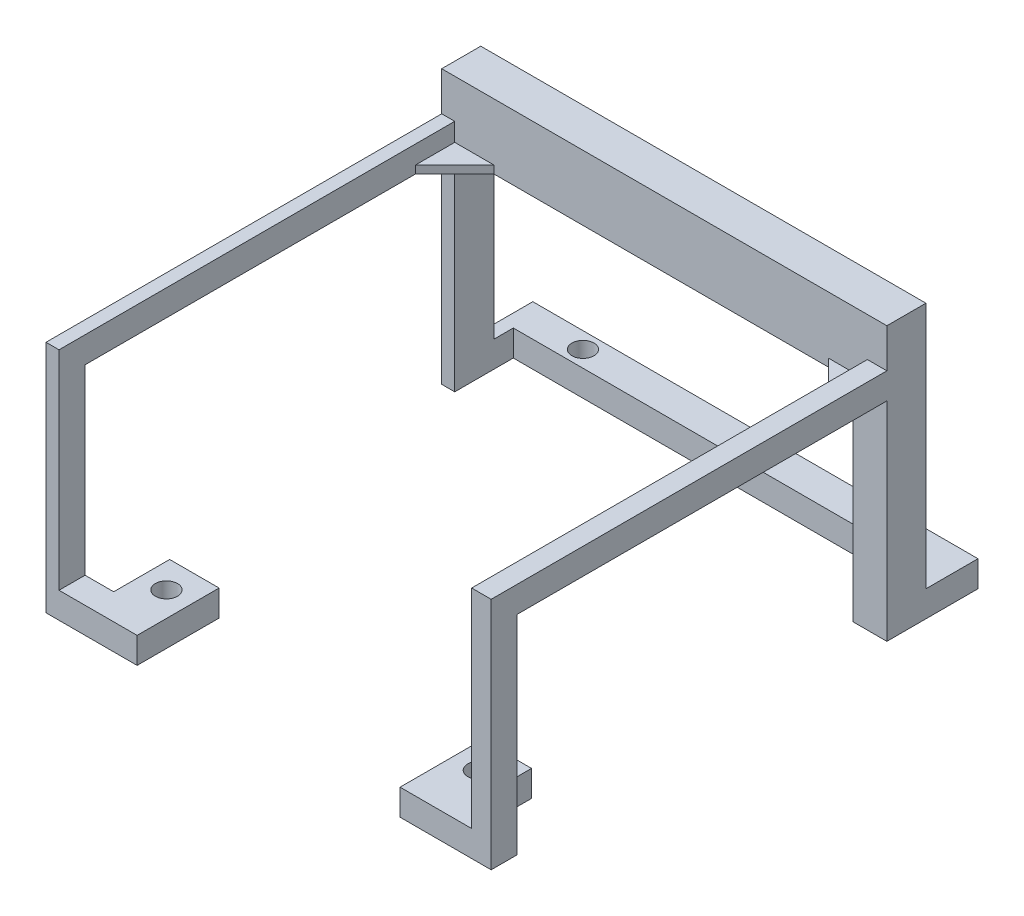
SolidWorks part; units mm, degrees
ref_plane "Front Plane" through (0, 0, 0) normal (0, 0, 1) x (1, 0, 0)
ref_plane "Top Plane" through (0, 0, 0) normal (0, 1, 0) x (1, 0, 0)
ref_plane "Right Plane" through (0, 0, 0) normal (1, 0, 0) x (0, 0, -1)
sketch "Sketch1" plane through (0, 0, 0) normal (0, 1, 0) x (1, 0, 0)
  line L0 (-55, 0) -> (55, 0) construction
  line L1 (-171, 12.5) -> (171, 12.5)
  line L3 (-158, 0) -> (158, 0)
  line L4 (171, 12.5) -> (171, 0)
  line L8 (-171, -12.5) -> (-158, -12.5)
  line L9 (-158, -12.5) -> (-158, 0)
  line L10 (0, -46.75) -> (0, 46.75) construction
  line L11 (171, -12.5) -> (158, -12.5)
  line L12 (158, -12.5) -> (158, 0)
  line L13 (171, 0) -> (171, -12.5)
  line L14 (-145.5, 6.25) -> (-145.5, 12.5) construction
  line L15 (-145.5, 6.25) -> (-145.5, 0) construction
  line L16 (-145.5, 0) -> (-158, 0) construction
  line L17 (-25.5, 6.25) -> (0, 6.25) construction
  line L18 (-145.5, 6.25) -> (-171, 6.25) construction
  line L19 (-171, 12.5) -> (-171, -12.5)
  circle A0 centre (-145.5, 6.25) radius 4.25
  circle A1 centre (145.5, 6.25) radius 4.25
  circle A2 centre (-25.5, 6.25) radius 4.25
  circle A3 centre (25.5, 6.25) radius 4.25
  point P6 (0, 0)
  dimension "D2" = 8.5
  dimension "D1" = 342
  dimension "D3" = 316
  dimension "D4" = 25
  dimension "D6" = 12.5
  dimension "D7" = 120
  dimension "D8" = 120
extrude "Boss-Extrude1" add sketch "Sketch1" along normal blind 10
sketch "Sketch2" plane through (0, 0, 12.5) normal (0, 0, 1) x (1, 0, 0)
  line L0 (-171, 0) -> (-171, 105)
  line L1 (-171, 10) -> (-171, 0) construction
  line L2 (-171, 105) -> (171, 105)
  line L3 (171, 105) -> (171, 0)
  line L4 (171, 10) -> (171, 0) construction
  line L5 (-171, 0) -> (-158, 0)
  line L6 (-158, 0) -> (-158, 80)
  line L7 (-158, 80) -> (158, 80)
  line L8 (158, 80) -> (158, 0)
  line L9 (-15.9953, 80) -> (-15.9953, 105) construction
  line L10 (-158, 52.4694) -> (-171, 52.4694) construction
  line L11 (55, 0) -> (-55, 0) construction
  line L12 (158, 0) -> (171, 0)
  line L16 (158, 0) -> (171, 0)
  line L17 (171, 0) -> (171, 10)
  line L18 (171, 10) -> (158, 10)
  line L19 (158, 10) -> (158, 0)
  line L21 (171, 0) -> (171, 10)
  line L23 (158, 10) -> (158, 0)
  dimension "D1" = 80
  dimension "D2" = 25
  dimension "D3" = 0
extrude "Boss-Extrude2" add sketch "Sketch2" against normal blind 5 and the other way blind 10
sketch "Sketch3" plane through (0, 0, 22.5) normal (0, 0, 1) x (1, 0, 0)
  line L0 (171, 105) -> (171, 0) construction
  line L1 (-171, 90) -> (171, 90)
  line L2 (-171, 90) -> (-171, 80)
  line L3 (-171, 80) -> (171, 80)
  line L4 (171, 90) -> (171, 80)
  line L5 (-158, 80) -> (158, 80) construction
  line L6 (-171, 0) -> (-171, 105) construction
  dimension "D1" = 10
extrude "Boss-Extrude3" add sketch "Sketch3" along normal blind 304
sketch "Sketch4" plane through (0, 105, 0) normal (0, 1, 0) x (1, 0, 0)
  line L2 (-171, -22.5) -> (171, -22.5) construction
  line L3 (-163.5, -22.5) -> (-5, -22.5)
  line L4 (-163.5, -22.5) -> (-163.5, -34.75)
  line L5 (-163.5, -326.5) -> (-5, -326.5)
  line L6 (163.5, -22.5) -> (163.5, -51.4723)
  line L8 (-163.5, -80.765) -> (-171, -80.765) construction
  line L9 (-171, -326.5) -> (-171, -22.5) construction
  line L10 (163.5, -70.9551) -> (171, -70.9551) construction
  line L11 (171, -326.5) -> (171, -22.5) construction
  line L12 (-5, -68.9608) -> (0, -68.9608) construction
  line L13 (171, -326.5) -> (-171, -326.5) construction
  line L14 (-163.5, -39.75) -> (-163.5, -326.5)
  line L19 (163.5, -51.4723) -> (163.5, -326.5)
  line L20 (5, -22.5) -> (163.5, -22.5)
  line L25 (43.2116, -39.75) -> (43.2116, -22.5) construction
  line L27 (-5, -22.5) -> (-5, -326.5)
  line L28 (5, -39.75) -> (5, -326.5)
  line L30 (5, -326.5) -> (163.5, -326.5)
  line L32 (5, -39.75) -> (5, -22.5)
  line L33 (-163.5, -34.75) -> (-163.5, -39.75)
  line L34 (171, -22.5) -> (-171, -22.5) construction
  line L35 (0, -46.75) -> (0, 46.75) construction
  line L36 (0, -68.9608) -> (5, -68.9608) construction
  dimension "D1" = 5
  dimension "D4" = 7.5
extrude "Cut-Extrude1" cut sketch "Sketch4" against normal up to next
ref_plane "Plane1" through (0, 0, 174.5) normal (0, 0, -1) x (-1, 0, 0)
mirror "Mirror3" about plane through (0, 0, 174.5) normal (0, 0, -1) of "Boss-Extrude2", "Boss-Extrude1"
mirror "Mirror4" about plane through (0, 0, 174.5) normal (0, 0, -1) of "Boss-Extrude1"
ref_plane "Plane2" through (0, 80, 0) normal (0, -1, 0) x (-1, 0, 0)
sketch "Sketch7" plane through (0, 80, 0) normal (0, -1, 0) x (-1, 0, 0)
  line L6 (-163.5, -22.5) -> (-148.5, -22.5)
  line L7 (-158, -22.5) -> (-171, -22.5) construction
  line L8 (-163.5, -22.5) -> (-163.5, -326.5) construction
  line L9 (-5, -22.5) -> (-158, -22.5) construction
  line L10 (-148.5, -22.5) -> (-163.5, -37.5)
  line L11 (-163.5, -37.5) -> (-163.5, -22.5)
  line L12 (-5, -22.5) -> (-20, -22.5)
  line L13 (-20, -22.5) -> (-5, -37.5)
  line L14 (-5, -326.5) -> (-5, -22.5) construction
  line L15 (-5, -37.5) -> (-5, -22.5)
  dimension "D1" = 15
extrude "Boss-Extrude4" add sketch "Sketch7" against normal blind 3
mirror "Mirror5" about plane through (0, 0, 174.5) normal (0, 0, -1) of "Boss-Extrude4" second plane through (0, 0, 0) second plane normal (1, 0, 0)
sketch "Sketch8" plane through (0, 0, 0) normal (1, 0, 0) x (0, 0, -1)
  line L0 (-326.5, 80) -> (-341.5, 80)
  line L1 (-22.5, 80) -> (-7.5, 80)
  line L2 (-349, 10) -> (-349, 0)
  line L3 (0, 10) -> (0, 0)
  line L16 (-361.5, 10) -> (-361.5, 0)
  line L17 (-361.5, 0) -> (-326.5, 0)
  line L18 (-326.5, 0) -> (-326.5, 80)
  line L19 (-326.5, 80) -> (-22.5, 80)
  line L20 (-22.5, 80) -> (-22.5, 0)
  line L21 (-22.5, 0) -> (12.5, 0)
  line L22 (12.5, 0) -> (12.5, 10)
  line L23 (12.5, 10) -> (-7.5, 10)
  line L24 (-7.5, 10) -> (-7.5, 105)
  line L25 (-7.5, 105) -> (-22.5, 105)
  line L26 (-22.5, 105) -> (-22.5, 90)
  line L27 (-22.5, 90) -> (-326.5, 90)
  line L28 (-326.5, 90) -> (-326.5, 105)
  line L29 (-326.5, 105) -> (-341.5, 105)
  line L30 (-341.5, 105) -> (-341.5, 10)
  line L31 (-341.5, 10) -> (-361.5, 10)
  line L33 (-349, 0) -> (-326.5, 0)
  line L34 (-326.5, 0) -> (-326.5, 80)
  line L36 (-22.5, 80) -> (-22.5, 0)
  line L37 (-22.5, 0) -> (0, 0)
  line L39 (0, 10) -> (-7.5, 10)
  line L40 (-7.5, 10) -> (-7.5, 80)
  line L46 (-341.5, 80) -> (-341.5, 10)
  line L47 (-341.5, 10) -> (-349, 10)
  dimension "D1" = 0
extrude "Boss-Extrude5" add sketch "Sketch8" along normal blind 5 and the other way blind 5
sketch "Sketch9" plane through (0, 0, 174.5) normal (0, 0, -1) x (-1, 0, 0)
  line L1 (-163.5, 10) -> (-136, 10)
  line L2 (-163.5, 80) -> (-163.5, 10)
  line L3 (-171, 80) -> (-171, 0)
  line L4 (-136, 10) -> (-136, 0)
  line L5 (-136, 0) -> (-171, 0)
  line L6 (-158, 0) -> (-171, 0) construction
  line L7 (-171, 80) -> (-163.5, 80)
  line L8 (-171, 10) -> (-171, 0) construction
  point P4 (0, 0)
  dimension "D1" = 35
extrude "Boss-Extrude6" add sketch "Sketch9" along normal blind 10
sketch "Sketch10" plane through (0, 10, 0) normal (0, 1, 0) x (1, 0, 0)
  line L0 (155, -164.5) -> (155, -143)
  line L1 (136, -164.5) -> (163.5, -164.5) construction
  line L2 (155, -143) -> (136, -143)
  line L3 (136, -143) -> (136, -164.5)
  line L4 (136, -164.5) -> (155, -164.5)
  line L5 (145.5, -153.75) -> (155, -153.75) construction
  line L6 (145.5, -153.75) -> (136, -153.75) construction
  line L7 (145.5, -153.75) -> (145.5, -143) construction
  line L8 (145.5, -153.75) -> (145.5, -164.5) construction
  circle A0 centre (145.5, -153.75) radius 4.25
  circle A1 centre (145.5, 6.25) radius 4.25 construction
  circle A2 centre (145.5, 6.25) radius 4.25 construction
  dimension "D1" = 160
extrude "Boss-Extrude7" add sketch "Sketch10" against normal blind 10
ref_plane "Plane3" through (85.5, 0, 0) normal (1, 0, 0) x (0, 0, -1)
mirror "Mirror6" about plane through (85.5, 0, 0) normal (1, 0, 0) of "Boss-Extrude6"
mirror "Mirror7" about plane through (85.5, 0, 0) normal (1, 0, 0) of "Boss-Extrude6", "Boss-Extrude7"
sketch "Sketch11" plane through (0, 0, 174.5) normal (0, 0, 1) x (1, 0, 0)
  line L0 (7.5, 80) -> (5, 80)
  line L1 (5, 80) -> (5, 10)
  line L2 (5, 10) -> (7.5, 10)
  line L3 (7.5, 10) -> (7.5, 80)
extrude "Cut-Extrude2" cut sketch "Sketch11" against normal up to next
mirror "Mirror8" about plane through (0, 0, 174.5) normal (0, 0, -1) of "Mirror7", "Mirror6", "Boss-Extrude6", "Boss-Extrude7"
mirror "Mirror9" about plane through (0, 0, 174.5) normal (0, 0, -1) of "Cut-Extrude2"
sketch "Sketch14" plane through (0, 0, 0) normal (1, 0, 0) x (0, 0, -1)
  line L1 (-433.126, 129.2099) -> (141.8228, 129.2099)
  line L2 (-433.126, 129.2099) -> (-433.126, -49.4047)
  line L3 (-433.126, -49.4047) -> (141.8228, -49.4047)
  line L4 (141.8228, 129.2099) -> (141.8228, -49.4047)
extrude "Cut-Extrude5" cut sketch "Sketch14" against normal up to next
sketch "Sketch15" plane through (0, 0, 174.5) normal (0, 0, -1) x (-1, 0, 0)
  line L1 (-218.083, 127.1937) -> (79.9101, 127.1937)
  line L2 (-218.083, 127.1937) -> (-218.083, -45.1397)
  line L3 (-218.083, -45.1397) -> (79.9101, -45.1397)
  line L4 (79.9101, 127.1937) -> (79.9101, -45.1397)
  point P4 (79.9101, -45.1397)
extrude "Cut-Extrude6" cut sketch "Sketch15" against normal up to next
